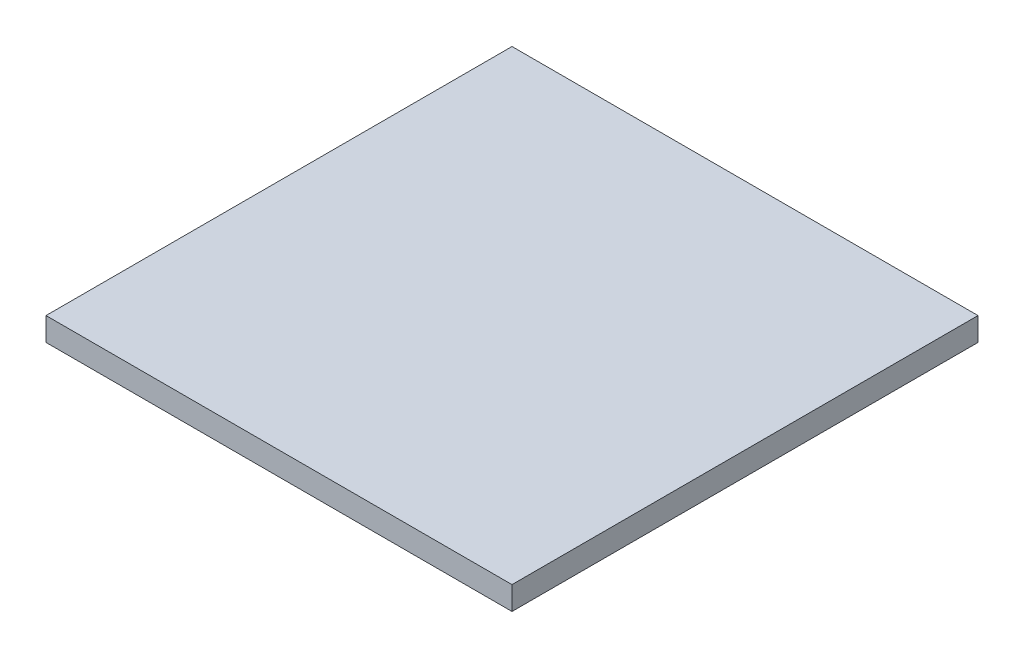
SolidWorks part; units mm, degrees
material "Glass"
ref_plane "Front Plane" through (0, 0, 0) normal (0, 0, 1) x (1, 0, 0)
ref_plane "Top Plane" through (0, 0, 0) normal (0, 1, 0) x (1, 0, 0)
ref_plane "Right Plane" through (0, 0, 0) normal (1, 0, 0) x (0, 0, -1)
sketch "Sketch1" plane through (0, 0, 0) normal (0, 1, 0) x (1, 0, 0)
  line L1 (0, 0) -> (40, 0)
  line L2 (0, 0) -> (0, 40)
  line L3 (0, 40) -> (40, 40)
  line L4 (40, 0) -> (40, 40)
  dimension "D1" = 40
  dimension "D2" = 40
extrude "Boss-Extrude1" add sketch "Sketch1" along normal blind 2
